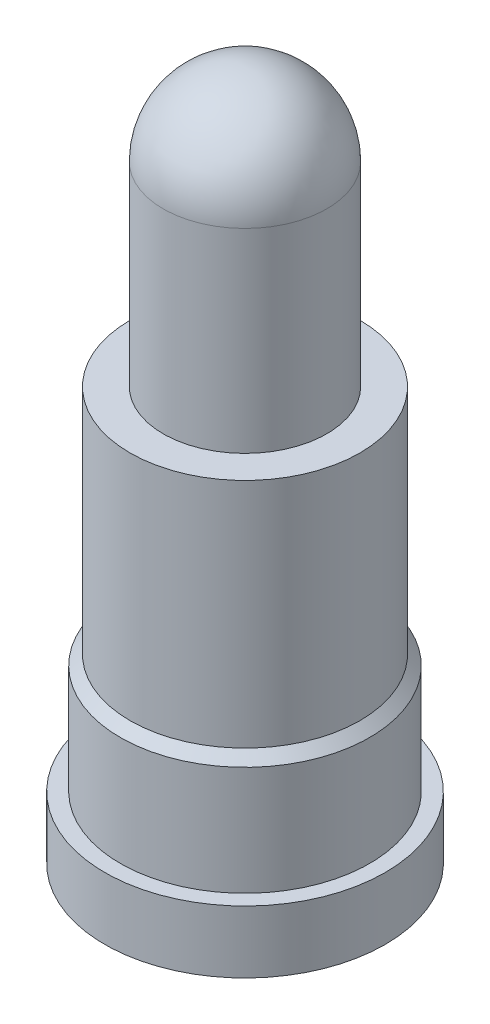
SolidWorks part; units mm, degrees
material "Aluminum Bronze"
ref_plane "Front Plane" through (0, 0, 0) normal (0, 0, 1) x (1, 0, 0)
ref_plane "Top Plane" through (0, 0, 0) normal (0, 1, 0) x (1, 0, 0)
ref_plane "Right Plane" through (0, 0, 0) normal (1, 0, 0) x (0, 0, -1)
sketch "Sketch3" plane through (0, 0, 0) normal (0, 0, 1) x (1, 0, 0)
  line L0 (0, 0) -> (-0.9144, 0)
  line L1 (-0.9144, 0) -> (-0.9144, 0.4064)
  line L2 (-0.9144, 0.4064) -> (-0.8128, 0.4064)
  line L3 (-0.8128, 0.4064) -> (-0.8128, 1.1176)
  line L4 (-0.8128, 1.1176) -> (-0.7493, 1.1811)
  line L5 (-0.7493, 1.1811) -> (-0.7493, 2.6924)
  line L6 (-0.7493, 2.6924) -> (-0.5334, 2.6924)
  line L7 (-0.5334, 2.6924) -> (-0.5334, 3.9624)
  line L8 (-0.5334, 3.9624) -> (0, 3.9624)
  line L9 (0, 3.9624) -> (0, 0)
  line L10 (-0.8128, 1.1176) -> (0, 1.1176) construction
  line L11 (0, 3.9624) -> (0, 4.4958)
  circle A0 centre (0, 3.9624) radius 0.5334
  point P12 (0, 4.4958)
  dimension "D1" = 0.9144
  dimension "D2" = 0.4064
  dimension "D3" = 0.8128
  dimension "D4" = 0.7112
  dimension "D5" = 0.7493
  dimension "D6" = 2.6924
  dimension "D7" = 0.5334
  dimension "D8" = 4.4958
  dimension "D9" = 45
revolve "Revolve1" add sketch "Sketch3" angle 360 about L9
